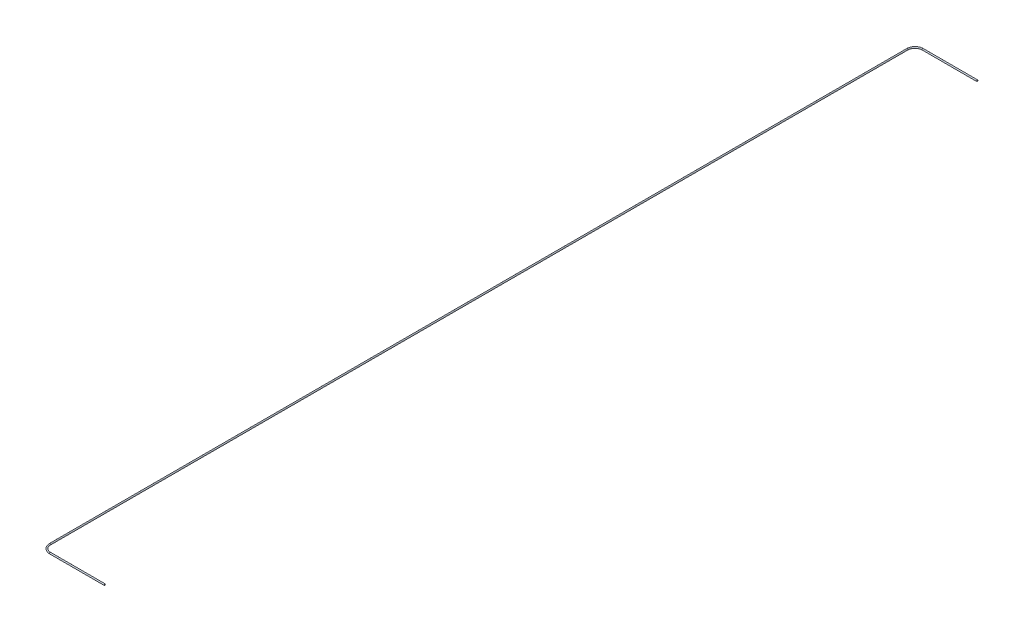
SolidWorks part; units mm, degrees
ref_plane "Front Plane" through (0, 0, 0) normal (0, 0, 1) x (1, 0, 0)
ref_plane "Top Plane" through (0, 0, 0) normal (0, 1, 0) x (1, 0, 0)
ref_plane "Right Plane" through (0, 0, 0) normal (1, 0, 0) x (0, 0, -1)
sketch "Sketch1" plane through (0, 0, 0) normal (0, 1, 0) x (1, 0, 0)
  line L0 (0, -4125) -> (0, 4125)
  line L1 (75, 4200) -> (600, 4200)
  line L2 (600, 0) -> (-674.806, 0) construction
  line L3 (75, -4200) -> (600, -4200)
  arc A0 (0, 4125) -> (75, 4200) centre (75, 4125) cw
  arc A1 (0, -4125) -> (75, -4200) centre (75, -4125) ccw
  point P6 (0, 4200)
  point P10 (0, 0)
  dimension "D3" = 75
  dimension "D1" = 4200
  dimension "D2" = 600
sweep "Sweep1" add path "Sketch1" circular profile diameter 12.7 parameters "D3"=12.7
